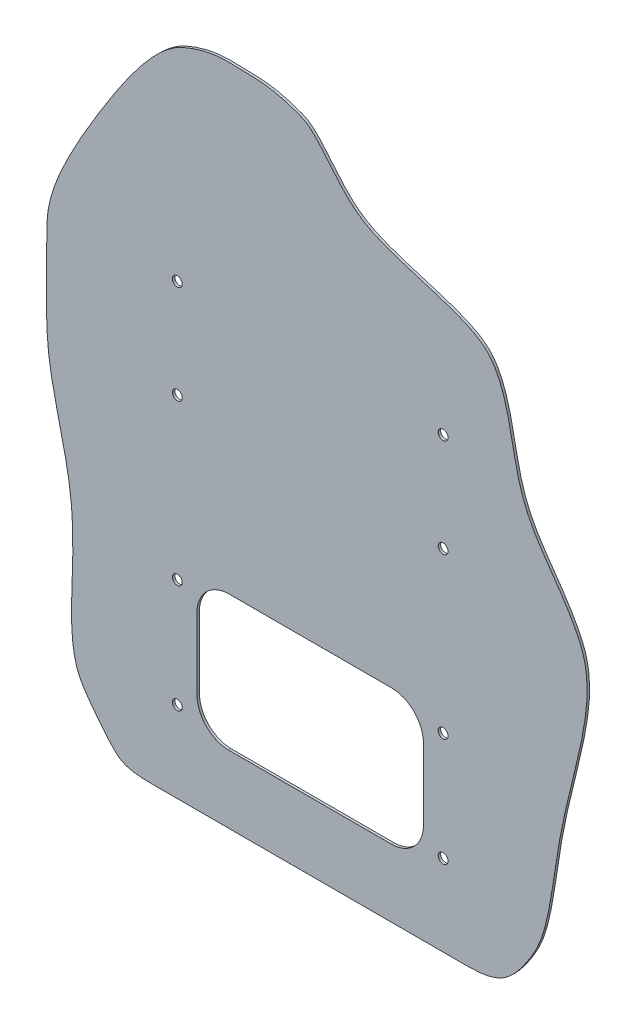
SolidWorks part; units mm, degrees
ref_plane "Ebene vorne" through (0, 0, 0) normal (0, 0, 1) x (1, 0, 0)
ref_plane "Ebene oben" through (0, 0, 0) normal (0, 1, 0) x (1, 0, 0)
ref_plane "Ebene rechts" through (0, 0, 0) normal (1, 0, 0) x (0, 0, -1)
sketch "Skizze1" plane through (0, 0, 0) normal (0, 0, 1) x (1, 0, 0)
  line L1 (32.5441, -145.8302) -> (26.3941, -140.6698) construction
  line L2 (23.1801, -139.5) -> (12.3, -139.5) construction
  line L3 (-35.758, -147) -> (-63.9382, -147) construction
  line L7 (32.5441, -145.8302) -> (26.3941, -140.6698) construction
  line L8 (23.1801, -139.5) -> (12.3, -139.5) construction
  line L9 (-63.9382, -137) -> (63.9382, -137)
  line L20 (37.5779, -137) -> (32.822, -133.0093) construction
  line L21 (23.1801, -129.5) -> (12.3, -129.5) construction
  line L22 (-12.3, -129.5) -> (-23.1801, -129.5) construction
  line L23 (-32.822, -133.0093) -> (-37.5779, -137) construction
  line L24 (-37.5779, -137) -> (-63.9382, -137) construction
  line L25 (-12.3, -139.5) -> (-23.1801, -139.5) construction
  line L26 (-35.758, -147) -> (-63.9382, -147) construction
  line L27 (-26.3941, -140.6698) -> (-32.5441, -145.8302) construction
  line L28 (63.9382, -137) -> (37.5779, -137) construction
  line L29 (63.9382, -147) -> (35.758, -147) construction
  arc A1 (26.3941, -140.6698) -> (23.1801, -139.5) centre (23.1801, -144.5) ccw construction
  arc A5 (26.3941, -140.6698) -> (23.1801, -139.5) centre (23.1801, -144.5) ccw construction
  arc A12 (32.822, -133.0093) -> (23.1801, -129.5) centre (23.1801, -144.5) ccw construction
  arc A13 (-23.1801, -129.5) -> (-32.822, -133.0093) centre (-23.1801, -144.5) ccw construction
  arc A14 (-37.5779, -137) -> (-37.5779, -137) centre (-37.5779, -137) ccw construction
  arc A15 (-23.1801, -139.5) -> (-26.3941, -140.6698) centre (-23.1801, -144.5) ccw construction
  arc A16 (-35.758, -147) -> (-32.5441, -145.8302) centre (-35.758, -142) ccw construction
  arc A17 (37.5779, -137) -> (37.5779, -137) centre (37.5779, -137) ccw construction
  arc A18 (32.5441, -145.8302) -> (35.758, -147) centre (35.758, -142) ccw construction
  spline S0 degree 3 poles (1915.99, -415.9918) (-161.8227, -8.1272) (-36.2219, -208.9718) (-111.8752, -107.3491) (-100.6905, -61.8391) (-118.6421, -11.3372) (-116.8472, 19.2686) (-117.3004, 48.3207) (-110.3517, 70.9332) (-69.8164, 131.4834) (-42.9871, 143.3304) (-26.1899, 142.1987) (-12.9057, 142.3576) (10.1085, 133.7695) (19.5255, 115.629) (44.9897, 103.8305) (90.2803, 97.8242) (91.1967, 38.9517) (107.6242, 25.0064) (129.4227, -15.6063) (110.1616, -62.3956) (107.1598, -111.0039) (41.4762, -223.2801) (11.0319, 47.8911) (-1923.2054, -319.7546) knots -0.696712 -0.696712 -0.696712 -0.696712 0.180256 0.217196 0.369404 0.474798 0.55876 0.575055 0.637752 0.664616 0.670474 0.69633 0.721181 0.726402 0.746087 0.752576 0.788839 0.830964 0.869174 0.878591 0.925129 0.953403 0.96089 1.204592 1.204592 1.204592 1.204592 only from (-63.9382, -147) to (63.9382, -147) construction
  spline S1 degree 3 poles (-63.9382, -147) (-81.0061, -147) (-85.6618, -142.5608) (-111.8752, -107.3491) (-100.6905, -61.8391) (-118.6421, -11.3372) (-116.8472, 19.2686) (-117.3004, 48.3207) (-110.3517, 70.9332) (-69.8164, 131.4834) (-42.9871, 143.3304) (-26.1899, 142.1987) (-12.9057, 142.3576) (10.1085, 133.7695) (19.5255, 115.629) (44.9897, 103.8305) (90.2803, 97.8242) (91.1967, 38.9517) (107.6242, 25.0064) (129.4227, -15.6063) (110.1616, -62.3956) (107.1598, -111.0039) (89.5626, -141.0837) (79.5947, -147) (63.9382, -147) knots 0 0 0 0 0.180256 0.217196 0.369404 0.474798 0.55876 0.575055 0.637752 0.664616 0.670474 0.69633 0.721181 0.726402 0.746087 0.752576 0.788839 0.830964 0.869174 0.878591 0.925129 0.953403 0.96089 1 1 1 1 construction
  spline S2 degree 1 poles (-63.9382, -137) (63.9382, -137) knots 0 0 1 1 construction
  spline S3 degree 3 poles (-63.9382, -137) (-64.2689, -137) (-64.9419, -136.9968) (-66.1965, -136.9776) (-67.6583, -136.9293) (-69.2268, -136.8327) (-71.0854, -136.6549) (-72.986, -136.3483) (-74.6936, -135.883) (-76.0224, -135.3385) (-77.2356, -134.65) (-78.5632, -133.6645) (-80.1296, -132.2224) (-81.9773, -130.2274) (-84.1358, -127.634) (-86.6032, -124.4613) (-89.0478, -121.2559) (-90.8568, -118.7575) (-92.0929, -116.9034) (-93.1696, -115.0784) (-94.0208, -113.3664) (-94.7383, -111.5497) (-95.5636, -108.8821) (-96.3299, -105.1116) (-96.8458, -99.9103) (-97.0126, -94.1215) (-96.925, -87.8352) (-96.7022, -81.1328) (-96.4783, -74.0849) (-96.4028, -66.7441) (-96.6215, -59.1815) (-97.5867, -48.7621) (-100.033, -36.3592) (-102.8812, -24.6925) (-104.8241, -15.7722) (-105.9862, -9.2903) (-106.7153, -3.0355) (-107.0844, 3.4836) (-107.196, 10.3044) (-107.158, 16.3183) (-107.1054, 21.3561) (-107.0709, 25.2591) (-107.0517, 29.2794) (-107.0827, 33.4769) (-107.0846, 37.3495) (-106.9004, 40.9816) (-106.4245, 44.6513) (-105.2188, 50.1121) (-102.7859, 57.0624) (-98.4042, 66.3535) (-93.9927, 74.6471) (-89.2584, 82.8059) (-84.765, 90.1633) (-81.0286, 96.1267) (-77.0244, 102.2495) (-72.7918, 108.3006) (-68.4004, 114.0253) (-63.9371, 119.1647) (-60.2627, 122.7377) (-57.4435, 125.0473) (-55.4293, 126.4765) (-53.5263, 127.6009) (-51.4966, 128.6005) (-49.4026, 129.4727) (-46.5731, 130.5061) (-43.4122, 131.4332) (-40.0042, 132.1251) (-36.885, 132.4959) (-33.909, 132.6366) (-30.9396, 132.6187) (-28.3805, 132.529) (-26.2048, 132.46) (-24.1609, 132.4038) (-21.7899, 132.3213) (-19.0833, 132.1311) (-16.2903, 131.7808) (-13.6957, 131.2838) (-11.3581, 130.7105) (-9.4506, 130.178) (-7.723, 129.639) (-6.2336, 129.1398) (-4.8359, 128.6422) (-3.5769, 128.1278) (-2.4903, 127.5884) (-1.8018, 127.1955) (-1.0996, 126.7314) (-0.0853, 125.9725) (1.285, 124.7777) (3.0574, 122.9775) (5.5505, 120.1721) (8.2133, 116.8994) (11.1215, 113.4343) (13.4763, 110.8028) (15.6441, 108.6342) (17.5456, 106.9582) (19.087, 105.7321) (20.693, 104.6035) (22.8135, 103.2813) (25.4245, 101.9128) (28.3833, 100.6226) (32.0715, 99.1774) (36.7657, 97.5445) (42.3229, 95.8154) (47.7536, 94.1996) (52.9532, 92.6182) (57.8191, 91.0003) (62.2365, 89.2949) (66.0899, 87.4741) (68.741, 85.8694) (70.5084, 84.5433) (71.6422, 83.5488) (72.6743, 82.4781) (73.9819, 80.8888) (75.4814, 78.6009) (77.0823, 75.3579) (78.9472, 70.4417) (80.7966, 63.3917) (82.5723, 54.231) (83.985, 47.3014) (85.2227, 42.7587) (86.1618, 39.7451) (88.031, 34.8238) (91.2612, 28.6649) (95.5279, 22.3068) (99.1811, 17.2001) (102.2038, 12.7409) (104.5265, 9.102) (106.9708, 4.9846) (108.8178, 1.4551) (110.0314, -1.3336) (110.7665, -3.3358) (111.3549, -5.3625) (112.29, -9.589) (112.7842, -16.5693) (111.7079, -27.3265) (109.2891, -39.2523) (106.1059, -52.1168) (103.3631, -63.4387) (101.4598, -72.8951) (99.9005, -82.2764) (98.6222, -91.231) (97.2214, -99.4704) (96.0278, -105.1919) (94.8597, -109.4949) (93.7995, -112.6157) (92.9457, -114.7729) (92.0085, -116.7926) (90.9473, -118.8041) (89.8066, -120.7584) (88.5971, -122.6764) (87.3934, -124.4787) (85.8461, -126.6506) (83.993, -128.9766) (81.8987, -131.1787) (79.2418, -133.4335) (76.6815, -134.9009) (73.6496, -135.9527) (71.4211, -136.4434) (69.3846, -136.7278) (67.7225, -136.8835) (66.2158, -136.9627) (64.9428, -136.9946) (64.27, -137) (63.9382, -137) knots 0 0 0 0 0.003906 0.007812 0.015625 0.023438 0.03125 0.046875 0.0625 0.078125 0.09375 0.109375 0.125 0.140625 0.15625 0.171875 0.1875 0.195312 0.203125 0.210938 0.21875 0.226562 0.234375 0.25 0.265625 0.28125 0.296875 0.3125 0.328125 0.34375 0.359375 0.375 0.40625 0.4375 0.453125 0.46875 0.484375 0.5 0.515625 0.53125 0.539062 0.546875 0.554688 0.5625 0.570312 0.578125 0.585938 0.59375 0.609375 0.617188 0.625 0.632812 0.636719 0.640625 0.644531 0.648438 0.652344 0.65625 0.660156 0.662109 0.664062 0.666016 0.667969 0.669922 0.671875 0.675781 0.679688 0.683594 0.6875 0.691406 0.695312 0.697266 0.699219 0.703125 0.707031 0.710938 0.714844 0.716797 0.71875 0.720703 0.72168 0.722656 0.724609 0.725586 0.726562 0.727539 0.728516 0.730469 0.732422 0.734375 0.738281 0.740234 0.742188 0.744141 0.745117 0.746094 0.74707 0.748047 0.75 0.751953 0.753906 0.757812 0.761719 0.765625 0.769531 0.773438 0.777344 0.78125 0.785156 0.787109 0.789062 0.791016 0.792969 0.796875 0.800781 0.804688 0.8125 0.820312 0.828125 0.830078 0.832031 0.835938 0.84375 0.851562 0.859375 0.863281 0.867188 0.871094 0.875 0.876953 0.878906 0.880859 0.882812 0.890625 0.898438 0.90625 0.914062 0.921875 0.925781 0.929688 0.9375 0.941406 0.945312 0.949219 0.951172 0.953125 0.955078 0.957031 0.958984 0.960938 0.962891 0.964844 0.96875 0.972656 0.976562 0.984375 0.988281 0.992188 0.994141 0.996094 0.998047 0.999023 1 1 1 1
  point P32 (0, 0)
  point P33 (0, 0)
  dimension "D1" = 10
extrude "Aufsatz-Linear austragen1" add sketch "Skizze1" along normal blind 1
sketch "Skizze2" plane through (0, 0, 0) normal (0, 0, 1) x (1, 0, 0)
  circle A0 centre (-54, 45) radius 1.5 construction
  circle A1 centre (-54, 5) radius 1.5 construction
  circle A2 centre (-54, -60) radius 1.5 construction
  circle A3 centre (-54, -104) radius 1.5 construction
  circle A4 centre (54, -104) radius 1.5 construction
  circle A5 centre (54, -60) radius 1.5 construction
  circle A6 centre (54, 5) radius 1.5 construction
  circle A7 centre (54, 45) radius 1.5 construction
  circle A8 centre (-54, 45) radius 1.5 construction
  circle A9 centre (-54, 5) radius 1.5 construction
  circle A10 centre (-54, -60) radius 1.5 construction
  circle A11 centre (-54, -104) radius 1.5 construction
  circle A12 centre (54, -104) radius 1.5 construction
  circle A13 centre (54, -60) radius 1.5 construction
  circle A14 centre (54, 5) radius 1.5 construction
  circle A15 centre (54, 45) radius 1.5 construction
  circle A16 centre (-54, 45) radius 2
  circle A17 centre (-54, 5) radius 2
  circle A18 centre (54, 45) radius 2
  circle A19 centre (54, 5) radius 2
  circle A20 centre (54, -60) radius 2
  circle A21 centre (54, -104) radius 2
  circle A22 centre (-54, -104) radius 2
  circle A23 centre (-54, -60) radius 2
  dimension "D1" = 4
extrude "Schnitt-Linear austragen4" cut sketch "Skizze2" against normal through all and the other way through all
sketch "Skizze3" plane through (0, 0, 0) normal (0, 0, -1) x (-1, 0, 0)
  line L0 (33, -59.5) -> (-33, -59.5) construction
  line L1 (33, -59.5) -> (-33, -59.5) construction
  line L2 (41, -96.5) -> (41, -67.5) construction
  line L3 (-33, -104.5) -> (33, -104.5) construction
  line L4 (-41, -67.5) -> (-41, -96.5) construction
  line L5 (41, -96.5) -> (41, -67.5) construction
  line L6 (-33, -104.5) -> (33, -104.5) construction
  line L7 (-41, -67.5) -> (-41, -96.5) construction
  line L8 (33, -54.5) -> (-33, -54.5)
  line L9 (-46, -67.5) -> (-46, -96.5)
  line L10 (-33, -109.5) -> (33, -109.5)
  line L11 (46, -96.5) -> (46, -67.5)
  arc A0 (41, -67.5) -> (33, -59.5) centre (33, -67.5) ccw construction
  arc A1 (33, -104.5) -> (41, -96.5) centre (33, -96.5) ccw construction
  arc A2 (-41, -96.5) -> (-33, -104.5) centre (-33, -96.5) ccw construction
  arc A3 (-33, -59.5) -> (-41, -67.5) centre (-33, -67.5) ccw construction
  arc A4 (41, -67.5) -> (33, -59.5) centre (33, -67.5) ccw construction
  arc A5 (33, -104.5) -> (41, -96.5) centre (33, -96.5) ccw construction
  arc A6 (-41, -96.5) -> (-33, -104.5) centre (-33, -96.5) ccw construction
  arc A7 (-33, -59.5) -> (-41, -67.5) centre (-33, -67.5) ccw construction
  arc A8 (46, -67.5) -> (33, -54.5) centre (33, -67.5) ccw
  arc A9 (-33, -54.5) -> (-46, -67.5) centre (-33, -67.5) ccw
  arc A10 (-46, -96.5) -> (-33, -109.5) centre (-33, -96.5) ccw
  arc A11 (33, -109.5) -> (46, -96.5) centre (33, -96.5) ccw
  dimension "D1" = 5
extrude "Schnitt-Linear austragen6" cut sketch "Skizze3" against normal through all
